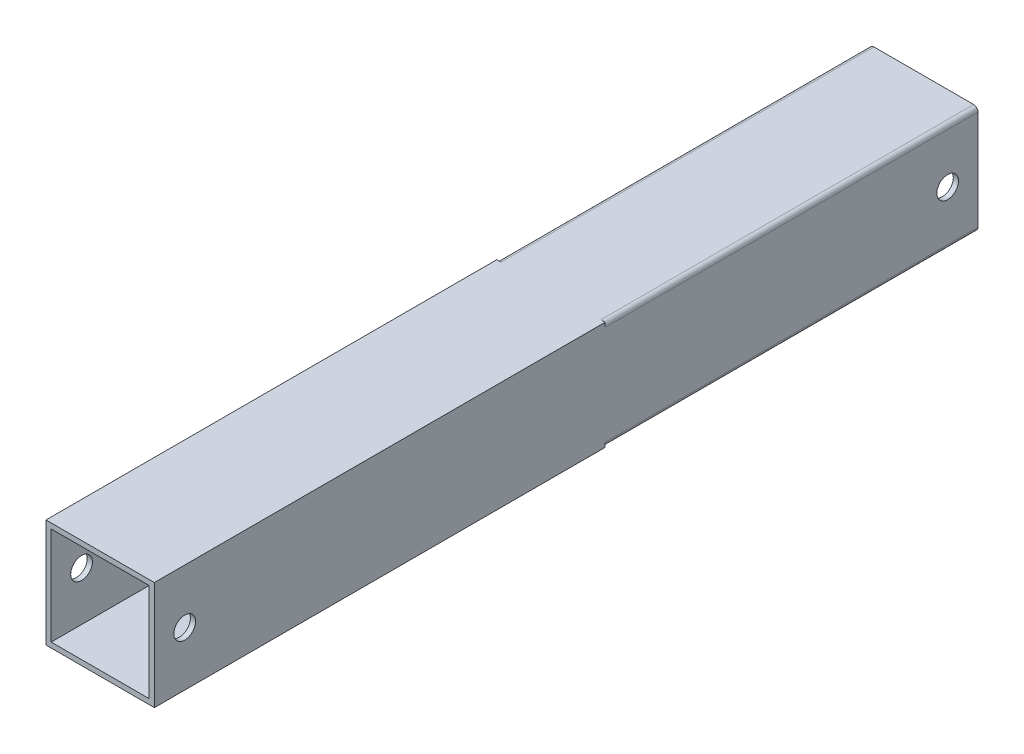
SolidWorks part; units mm, degrees
ref_plane "Alzado" through (0, 0, 0) normal (0, 0, 1) x (1, 0, 0)
ref_plane "Planta" through (0, 0, 0) normal (0, 1, 0) x (1, 0, 0)
ref_plane "Vista lateral" through (0, 0, 0) normal (1, 0, 0) x (0, 0, -1)
sketch "Croquis1" plane through (0, 0, 0) normal (0, 0, 1) x (1, 0, 0)
  line L0 (-11.3, 11.3) -> (11.3, 11.3)
  line L1 (-12.5, 12.5) -> (12.5, 12.5)
  line L2 (-12.5, 12.5) -> (-12.5, -12.5)
  line L3 (-12.5, -12.5) -> (12.5, -12.5)
  line L4 (12.5, 12.5) -> (12.5, -12.5)
  line L5 (-12.5, 12.5) -> (12.5, -12.5) construction
  line L6 (-12.5, -12.5) -> (12.5, 12.5) construction
  line L7 (11.3, 11.3) -> (11.3, -11.3)
  line L8 (-11.3, -11.3) -> (11.3, -11.3)
  line L9 (-11.3, 11.3) -> (-11.3, -11.3)
  point P0 (0, 0)
  dimension "D1" = 25
  dimension "D2" = 25
  dimension "D3" = 1.2
extrude "Saliente-Extruir1" add sketch "Croquis1" along normal blind 190
sketch "Croquis2" plane through (12.5, 0, 0) normal (1, 0, 0) x (0, 0, -1)
  line L0 (0, 0) -> (-190, 0) construction
  line L1 (0, -12.5) -> (0, 12.5) construction
  line L2 (-190, -12.5) -> (-190, 12.5) construction
  circle A0 centre (-7, 0) radius 2.5
  circle A1 centre (-183, 0) radius 2.5
  dimension "D1" = 5
  dimension "D3" = 5
  dimension "D4" = 7
  dimension "D2" = 7
extrude "Cortar-Extruir1" cut sketch "Croquis2" against normal through all
sketch "Croquis3" plane through (0, 0, 0) normal (0, 0, -1) x (-1, 0, 0)
  line L1 (-11.5, 12.5) -> (11.5, 12.5)
  line L2 (-12.5, 11.5) -> (-12.5, -11.5)
  line L3 (-11.5, -12.5) -> (11.5, -12.5)
  line L4 (12.5, 11.5) -> (12.5, -11.5)
  arc A0 (11.5, 12.5) -> (12.5, 11.5) centre (11.5, 11.5) cw
  circle A1 centre (0, 0) radius 40
  arc A2 (12.5, -11.5) -> (11.5, -12.5) centre (11.5, -11.5) cw
  arc A3 (-12.5, -11.5) -> (-11.5, -12.5) centre (-11.5, -11.5) ccw
  arc A4 (-12.5, 11.5) -> (-11.5, 12.5) centre (-11.5, 11.5) cw
  point P13 (12.5, -12.5)
  point P18 (-12.5, 12.5)
  dimension "D1" = 1
  dimension "D2" = 80
extrude "Cortar-Extruir2" cut sketch "Croquis3" against normal blind 86
sketch "Croquis4" plane through (0, 12.5, 0) normal (0, 1, 0) x (1, 0, 0)
  line L0 (12.5, -149.8351) -> (-12.5, -149.8351) construction
  line L3 (12.5, -190) -> (12.5, -86) construction
  line L4 (-12.5, -190) -> (-12.5, -86) construction
  text T0 "FRONT" font "Arial" height 3.5
